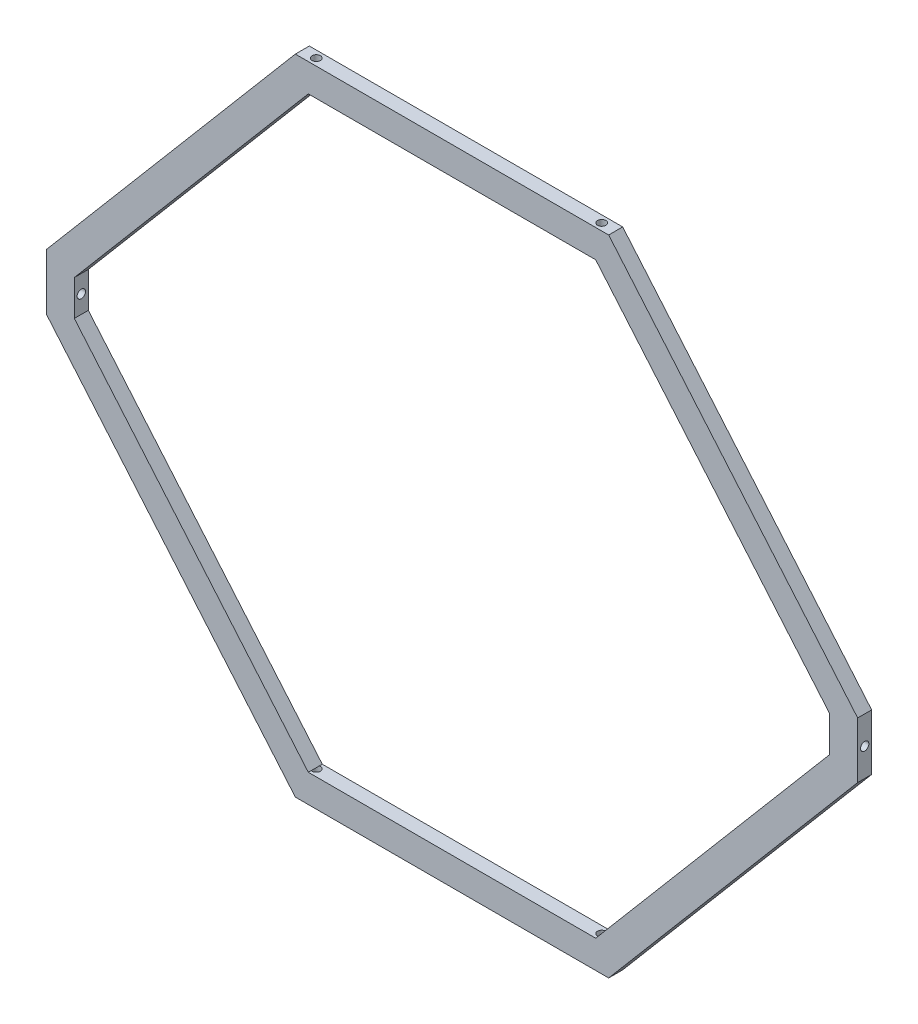
SolidWorks part; units mm, degrees
ref_plane "前视基准面" through (0, 0, 0) normal (0, 0, 1) x (1, 0, 0)
ref_plane "上视基准面" through (0, 0, 0) normal (0, 1, 0) x (1, 0, 0)
ref_plane "右视基准面" through (0, 0, 0) normal (1, 0, 0) x (0, 0, -1)
sketch "草图1" plane through (0, 0, 0) normal (0, 0, 1) x (1, 0, 0)
  line L0 (0, 0) -> (112, 0)
  line L1 (-89, -105) -> (0, 0)
  line L2 (56, -230) -> (112, -230)
  line L3 (56, -230) -> (0, -230)
  line L4 (112, 0) -> (201, -105)
  line L5 (201, -125) -> (112, -230)
  line L6 (-89, -115) -> (-89, -125)
  line L7 (201, -115) -> (201, -125)
  line L8 (201, -115) -> (201, -105)
  line L9 (-89, -115) -> (-89, -105)
  line L10 (0, -230) -> (-89, -125)
  line L11 (4.6328, -10) -> (107.3672, -10)
  line L12 (107.3672, -10) -> (191, -108.6679)
  line L13 (191, -115) -> (191, -108.6679)
  line L14 (191, -115) -> (191, -121.3321)
  line L15 (191, -121.3321) -> (107.3672, -220)
  line L16 (56, -220) -> (107.3672, -220)
  line L17 (56, -220) -> (4.6328, -220)
  line L18 (4.6328, -220) -> (-79, -121.3321)
  line L19 (-79, -115) -> (-79, -121.3321)
  line L20 (-79, -115) -> (-79, -108.6679)
  line L21 (-79, -108.6679) -> (4.6328, -10)
  dimension "D1" = 10
extrude "凸台-拉伸1" add sketch "草图1" along normal blind 5
sketch "草图2" plane through (0, 0, 0) normal (0, 1, 0) x (1, 0, 0)
  circle A0 centre (5, -2.5) radius 1.5
  circle A1 centre (107, -2.5) radius 1.5
extrude "切除-拉伸1" cut sketch "草图2" against normal blind 10
sketch "草图3" plane through (0, -230, 0) normal (0, -1, 0) x (1, 0, 0)
  circle A0 centre (5, 2.5) radius 1.5
  circle A1 centre (107, 2.5) radius 1.5
extrude "切除-拉伸2" cut sketch "草图3" against normal blind 10
sketch "草图4" plane through (-89, 0, 0) normal (-1, 0, 0) x (0, 0, 1)
  circle A0 centre (2.5, -115) radius 1.5
extrude "切除-拉伸3" cut sketch "草图4" against normal blind 10
sketch "草图5" plane through (201, 0, 0) normal (1, 0, 0) x (0, 0, -1)
  circle A0 centre (-2.5, -115) radius 1.5
extrude "切除-拉伸4" cut sketch "草图5" against normal blind 10
